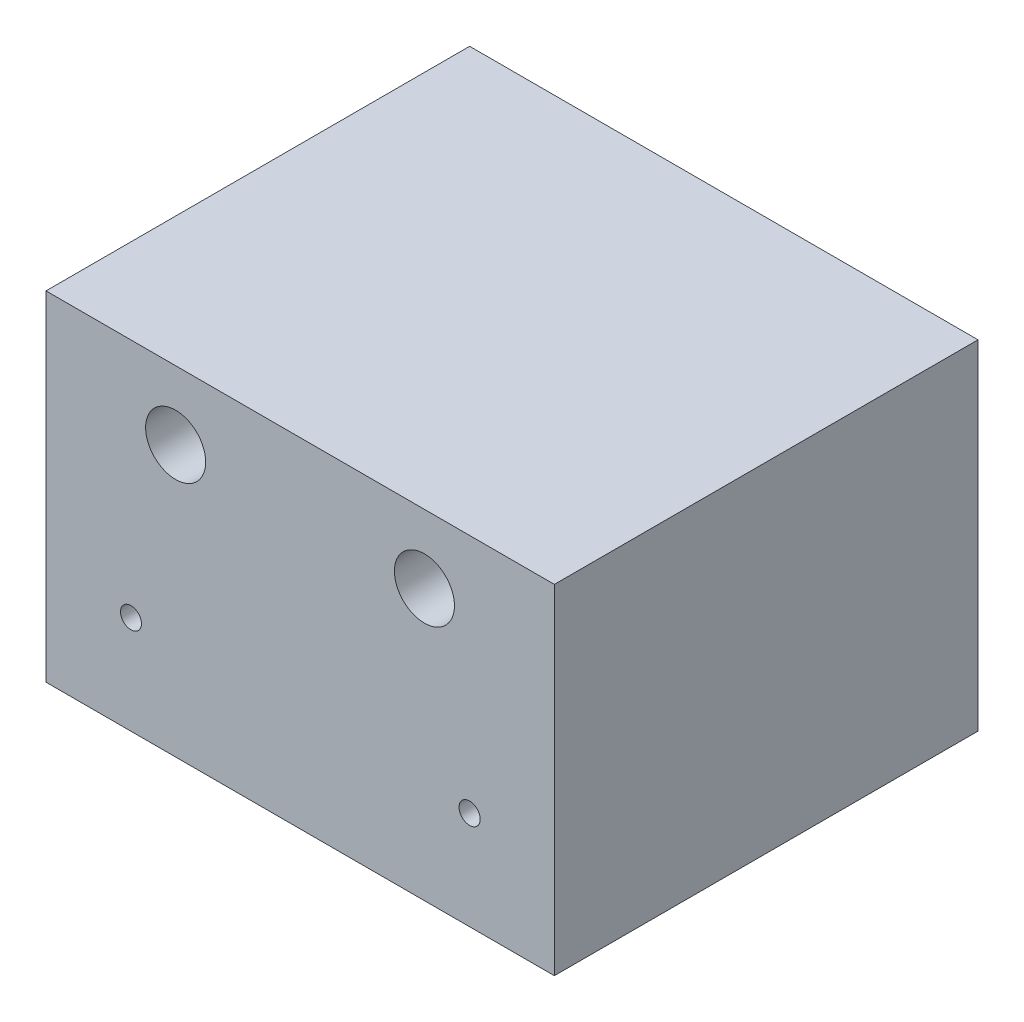
SolidWorks part; units mm, degrees
ref_plane "Front Plane" through (0, 0, 0) normal (0, 0, 1) x (1, 0, 0)
ref_plane "Top Plane" through (0, 0, 0) normal (0, 1, 0) x (1, 0, 0)
ref_plane "Right Plane" through (0, 0, 0) normal (1, 0, 0) x (0, 0, -1)
sketch "Sketch2" plane through (0, 0, 0) normal (0, 0, 1) x (1, 0, 0)
  line L0 (-38.9521, 81.0614) -> (0, 81.0614)
  line L1 (-152.4, 101.6) -> (0, 101.6)
  line L2 (-152.4, 101.6) -> (-152.4, 0)
  line L3 (-152.4, 0) -> (0, 0)
  line L4 (0, 101.6) -> (0, 0)
  line L5 (-20.32, 49.8791) -> (-132.08, 49.8791)
  line L6 (-20.32, 49.8791) -> (-20.32, 9.2391)
  line L7 (-20.32, 9.2391) -> (-132.08, 9.2391)
  line L8 (-132.08, 49.8791) -> (-132.08, 9.2391)
  line L9 (-113.538, 81.0614) -> (-152.4, 81.0614)
  line L10 (-76.2, 9.2391) -> (-76.2, 49.8791)
  line L11 (-76.2, 29.4837) -> (-25.4, 29.4837)
  line L12 (-76.2, 29.4837) -> (-126.9236, 29.4837)
  circle A0 centre (-113.538, 81.0614) radius 9
  circle A1 centre (-38.9521, 81.0614) radius 9
  circle A2 centre (-25.4, 29.4837) radius 3.175
  circle A3 centre (-126.9236, 29.4837) radius 3.1422
  point P4 (-76.2, 9.2391)
  point P6 (-76.2, 0)
  dimension "D5" = 18
  dimension "D6" = 18
  dimension "D10" = 6.35
  dimension "D1" = 152.4
  dimension "D2" = 101.6
  dimension "D3" = 111.76
  dimension "D4" = 40.64
  dimension "D7" = 38.9521
  dimension "D8" = 38.862
  dimension "D9" = 50.8
extrude "Boss-Extrude1" add sketch "Sketch2" along normal blind 127
sketch "Sketch3" plane through (0, 101.6, 0) normal (0, 1, 0) x (1, 0, 0)
  line L0 (-76.9406, -32.9999) -> (-76.9406, 0)
  line L1 (-136.0858, -32.9999) -> (-17.7955, -32.9999)
  line L2 (-136.0858, -32.9999) -> (-136.0858, -83.3632)
  line L3 (-136.0858, -83.3632) -> (-17.7955, -83.3632)
  line L4 (-17.7955, -32.9999) -> (-17.7955, -83.3632)
  line L5 (-152.4, 0) -> (0, 0) construction
  line L6 (-76.9406, -83.3632) -> (-76.9406, -127)
  line L7 (-152.4, -127) -> (0, -127) construction
  dimension "D1" = 32.9999
